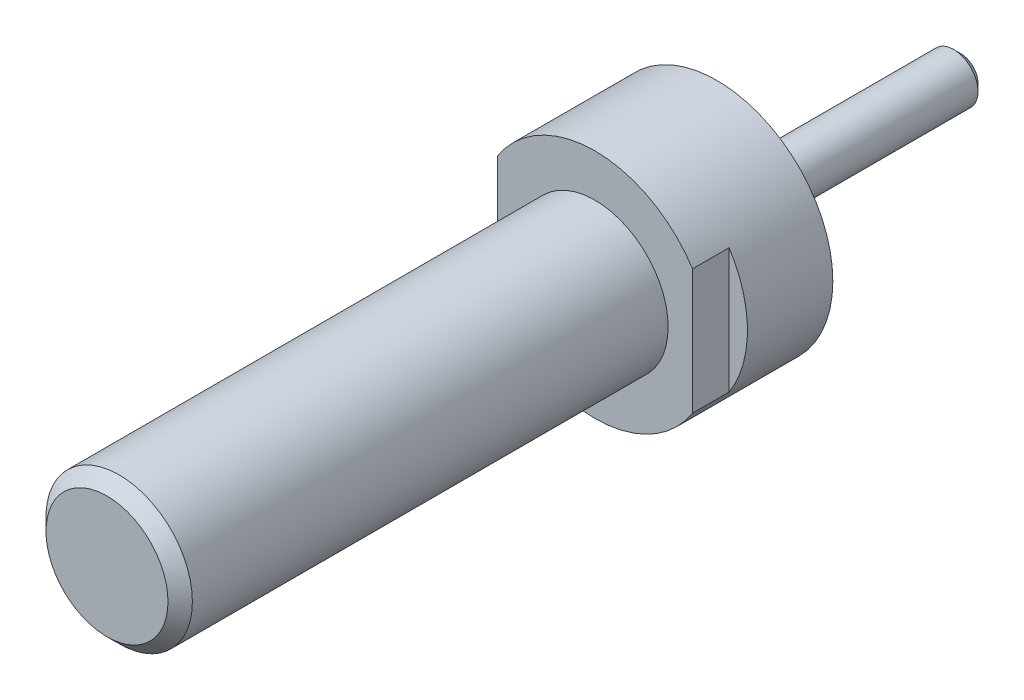
SolidWorks part; units mm, degrees
ref_plane "Спереди" through (0, 0, 0) normal (0, 0, 1) x (1, 0, 0)
ref_plane "Сверху" through (0, 0, 0) normal (0, 1, 0) x (1, 0, 0)
ref_plane "Справа" through (0, 0, 0) normal (1, 0, 0) x (0, 0, -1)
sketch "Эскиз1" plane through (0, 0, 0) normal (0, 0, 1) x (1, 0, 0)
  circle A0 centre (0, 0) radius 1
  dimension "D1" = 2
extrude "Вытянуть1" add sketch "Эскиз1" along normal blind 10
sketch "Эскиз2" plane through (0, 0, 10) normal (0, 0, 1) x (1, 0, 0)
  circle A0 centre (0, 0) radius 4.75
  dimension "D1" = 9.5
extrude "Вытянуть2" add sketch "Эскиз2" along normal blind 5
sketch "Эскиз3" plane through (0, 0, 15) normal (0, 0, 1) x (1, 0, 0)
  line L0 (-4, 3.6416) -> (-4, -3.6416)
  line L1 (0, 4.5883) -> (0, -4.4207) construction
  arc A0 (-4, 3.6416) -> (-4, -3.6416) centre (0, 0) ccw
  dimension "D1" = 4
extrude "Вырез-Вытянуть1" cut sketch "Эскиз3" against normal blind 1.5
sketch "Эскиз4" plane through (0, 0, 15) normal (0, 0, 1) x (1, 0, 0)
  line L0 (4, 4.2188) -> (4, -3.977)
  line L1 (-4, -2.5617) -> (-4, 2.5617) construction
  line L3 (4, 4.2188) -> (6.5803, 4.2188)
  line L4 (6.5803, 4.2188) -> (6.5803, -3.977)
  line L5 (6.5803, -3.977) -> (4, -3.977)
  dimension "D1" = 8
extrude "Вырез-Вытянуть3" cut sketch "Эскиз4" against normal blind 1.5
sketch "Эскиз5" plane through (0, 0, 15) normal (0, 0, 1) x (1, 0, 0)
  circle A0 centre (0, 0) radius 3
  dimension "D1" = 6
extrude "Вытянуть3" add sketch "Эскиз5" along normal blind 20
cosmetic thread "Условное изображение резьбы1" parameters "D1"=19, "D2"=5
chamfer "Фаска1" distance 0.5 angle 45
chamfer "Фаска2" distance 0.3 angle 45
